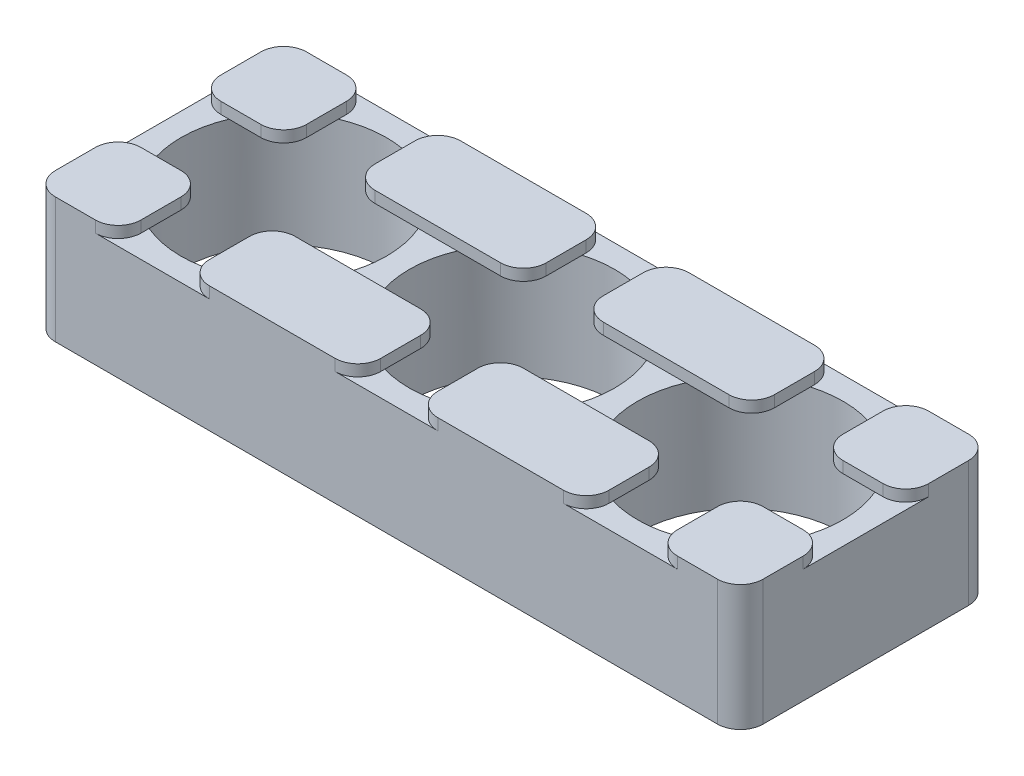
SolidWorks part; units mm, degrees
ref_plane "Front Plane" through (0, 0, 0) normal (0, 0, 1) x (1, 0, 0)
ref_plane "Top Plane" through (0, 0, 0) normal (0, 1, 0) x (1, 0, 0)
ref_plane "Right Plane" through (0, 0, 0) normal (1, 0, 0) x (0, 0, -1)
sketch "Sketch1" plane through (0, 0, 0) normal (0, 1, 0) x (1, 0, 0)
  line L1 (-11, 11) -> (51, 11)
  line L2 (-11, 11) -> (-11, -11)
  line L3 (-11, -11) -> (51, -11)
  line L4 (51, 11) -> (51, -11)
  circle A0 centre (0, 0) radius 9
  circle A1 centre (20, 0) radius 9
  circle A2 centre (40, 0) radius 9
  point P17 (-11, 0)
  dimension "D1" = 18
  dimension "D3" = 20
  dimension "D4" = 11
  dimension "D5" = 11
  dimension "D6" = 11
  dimension "D2" = 3
extrude "Boss-Extrude3" add sketch "Sketch1" along normal blind 10
sketch "Sketch3" plane through (0, 0, 0) normal (0, 1, 0) x (-1, 0, 0)
  line L0 (11, 11) -> (-51, 11) construction
  line L1 (11, 11) -> (3.5, 11)
  line L2 (11, 11) -> (11, 3.5)
  line L3 (11, 3.5) -> (3.5, 3.5)
  line L4 (3.5, 11) -> (3.5, 3.5)
  line L5 (-17.5, 11) -> (-2.5, 11)
  line L6 (-17.5, 11) -> (-17.5, 3.5)
  line L7 (-17.5, 3.5) -> (-2.5, 3.5)
  line L8 (-2.5, 11) -> (-2.5, 3.5)
  line L9 (9, 0) -> (-29, 0) construction
  line L10 (-37.5, 11) -> (-37.5, 3.5)
  line L11 (-37.5, 11) -> (-22.5, 11)
  line L12 (-22.5, 11) -> (-22.5, 3.5)
  line L13 (-37.5, 3.5) -> (-22.5, 3.5)
  line L26 (-20, 11) -> (-20, -11) construction
  line L27 (-51, -11) -> (-51, -3.5)
  line L28 (-51, -11) -> (-43.5, -11)
  line L29 (-51, -11) -> (11, -11) construction
  line L30 (11, 0) -> (-51, 0) construction
  line L31 (11, -11) -> (11, 11) construction
  line L32 (-51, 11) -> (-51, -11) construction
  line L33 (-51, 3.5) -> (-43.5, 3.5)
  line L34 (-43.5, 11) -> (-43.5, 3.5)
  line L35 (-51, 11) -> (-43.5, 11)
  line L36 (-51, 11) -> (-51, 3.5)
  line L37 (-43.5, -11) -> (-43.5, -3.5)
  line L38 (-51, -3.5) -> (-43.5, -3.5)
  line L51 (-37.5, -3.5) -> (-22.5, -3.5)
  line L52 (-22.5, -11) -> (-22.5, -3.5)
  line L53 (-37.5, -11) -> (-22.5, -11)
  line L54 (-37.5, -11) -> (-37.5, -3.5)
  line L55 (-2.5, -11) -> (-2.5, -3.5)
  line L56 (-17.5, -3.5) -> (-2.5, -3.5)
  line L57 (-17.5, -11) -> (-17.5, -3.5)
  line L58 (-17.5, -11) -> (-2.5, -11)
  line L59 (3.5, -11) -> (3.5, -3.5)
  line L60 (11, -3.5) -> (3.5, -3.5)
  line L61 (11, -11) -> (11, -3.5)
  line L62 (11, -11) -> (3.5, -11)
  line L63 (-51, -11) -> (11, -11) construction
  line L64 (11, 11) -> (-51, 11) construction
  circle A0 centre (0, 0) radius 9 construction
  circle A1 centre (-20, 0) radius 9 construction
  point P18 (-10, 11)
  point P19 (-10, 0)
  point P25 (-20, 11)
  point P78 (17.5516, 4.4484)
  point P79 (0, 0)
  point P80 (0, 0)
  point P81 (3.1257, -11)
  dimension "D1" = 7.5
  dimension "D2" = 15
  dimension "D4" = 20
  dimension "D3" = 2
extrude "Boss-Extrude4" add sketch "Sketch3" along normal blind 1 from surface at 10 starting at face at (20, 10, 9)
fillet "Fillet3" radius 2 32 edges at (37.5, 10.5, 11) (22.5, 10.5, 11) (22.5, 10.5, 3.5) (37.5, 10.5, 3.5) (17.5, 10.5, 11) (2.5, 10.5, 11) (2.5, 10.5, 3.5) (17.5, 10.5, 3.5) (-3.5, 10.5, 11) (-11, 5.5, 11) (-11, 10.5, 3.5) (-3.5, 10.5, 3.5) (-11, 10.5, -3.5) (-11, 5.5, -11) (-3.5, 10.5, -11) (-3.5, 10.5, -3.5) (2.5, 10.5, -3.5) (2.5, 10.5, -11) (17.5, 10.5, -11) (17.5, 10.5, -3.5) (37.5, 10.5, -11) (22.5, 10.5, -3.5) (22.5, 10.5, -11) (37.5, 10.5, -3.5) (43.5, 10.5, -3.5) (43.5, 10.5, -11) (51, 5.5, -11) (51, 10.5, -3.5) (43.5, 10.5, 3.5) (51, 5.5, 11) (43.5, 10.5, 11) (51, 10.5, 3.5)
